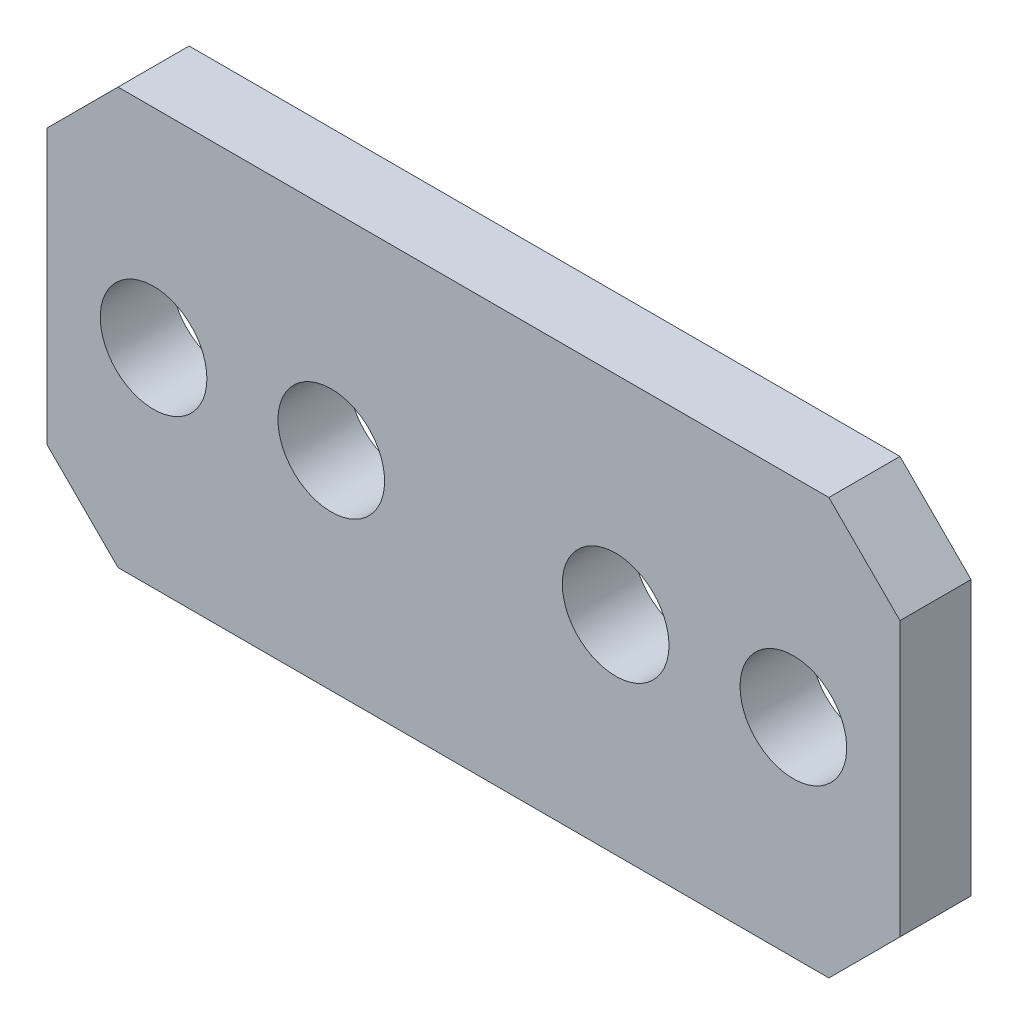
SolidWorks part; units mm, degrees
ref_plane "前视基准面" through (0, 0, 0) normal (0, 0, 1) x (1, 0, 0)
ref_plane "上视基准面" through (0, 0, 0) normal (0, 1, 0) x (1, 0, 0)
ref_plane "右视基准面" through (0, 0, 0) normal (1, 0, 0) x (0, 0, -1)
sketch "Sketch1" plane through (0, 0, 0) normal (0, 0, 1) x (1, 0, 0)
  line L0 (0, 4.4823) -> (0, 0) construction
  line L1 (-12, 5.8542) -> (12, 5.8542)
  line L2 (-12, 5.8542) -> (-12, -5.8542)
  line L3 (-12, -5.8542) -> (12, -5.8542)
  line L4 (12, 5.8542) -> (12, -5.8542)
  line L5 (-12, 5.8542) -> (12, -5.8542) construction
  line L6 (-12, -5.8542) -> (12, 5.8542) construction
  circle A2 centre (-9, 0) radius 1.5
  circle A3 centre (-4, 0) radius 1.5
  circle A4 centre (4, 0) radius 1.5
  circle A5 centre (9, 0) radius 1.5
  point P0 (0, 0)
  dimension "D3" = 3
  dimension "D4" = 3
  dimension "D6" = 5
  dimension "D2" = 24
  dimension "D5" = 3
extrude "Boss-Extrude1" add sketch "Sketch1" along normal blind 2
chamfer "Chamfer1" distance 2 angle 45 4 edges at (12, 5.8542, 1) (12, -5.8542, 1) (-12, -5.8542, 1) (-12, 5.8542, 1)
